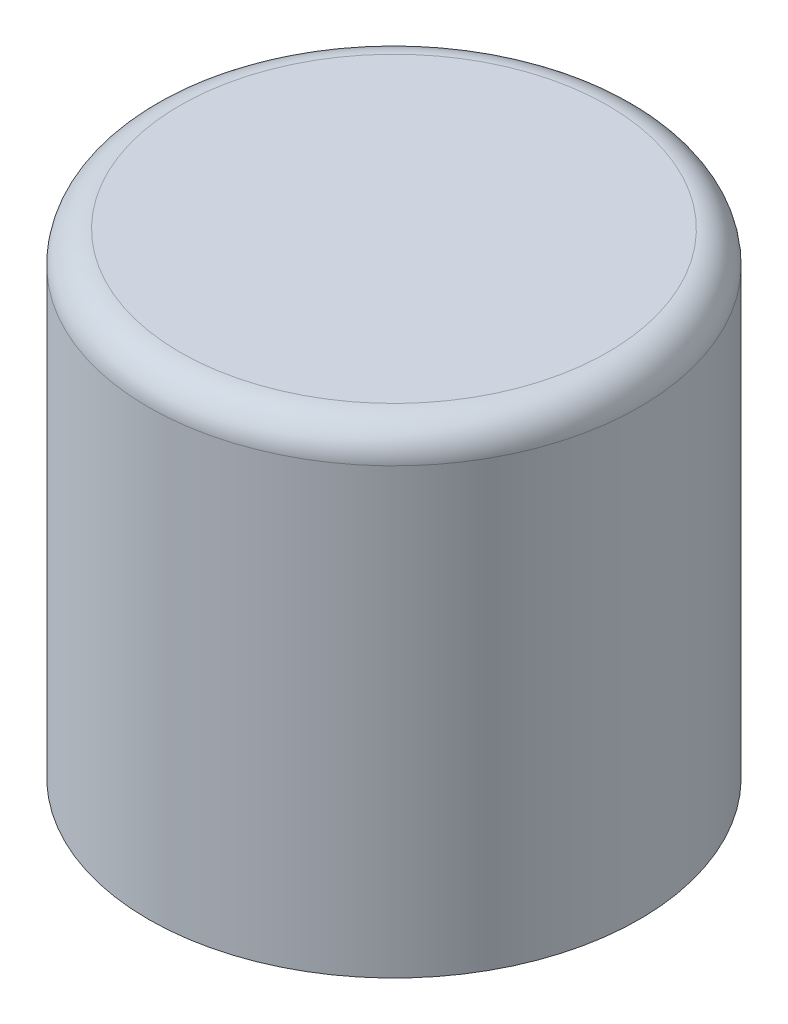
SolidWorks part; units mm, degrees
ref_plane "前视基准面" through (0, 0, 0) normal (0, 0, 1) x (1, 0, 0)
ref_plane "上视基准面" through (0, 0, 0) normal (0, 1, 0) x (1, 0, 0)
ref_plane "右视基准面" through (0, 0, 0) normal (1, 0, 0) x (0, 0, -1)
sketch "草图1" plane through (0, 0, 0) normal (0, 1, 0) x (1, 0, 0)
  circle A0 centre (0, 0) radius 3.1
  circle A1 centre (0, 0) radius 1.7
  dimension "D1" = 6.2
  dimension "D2" = 3.4
extrude "凸台-拉伸1" add sketch "草图1" along normal blind 5
sketch "草图2" plane through (0, 5, 0) normal (0, 1, 0) x (1, 0, 0)
  circle A1 centre (0, 0) radius 3.1
  circle A2 centre (0, 0) radius 3.1
  dimension "D1" = 0
extrude "凸台-拉伸2" add sketch "草图2" along normal blind 1
fillet "圆角1" radius 0.4 1 edges at (0, 6, 3.1)
